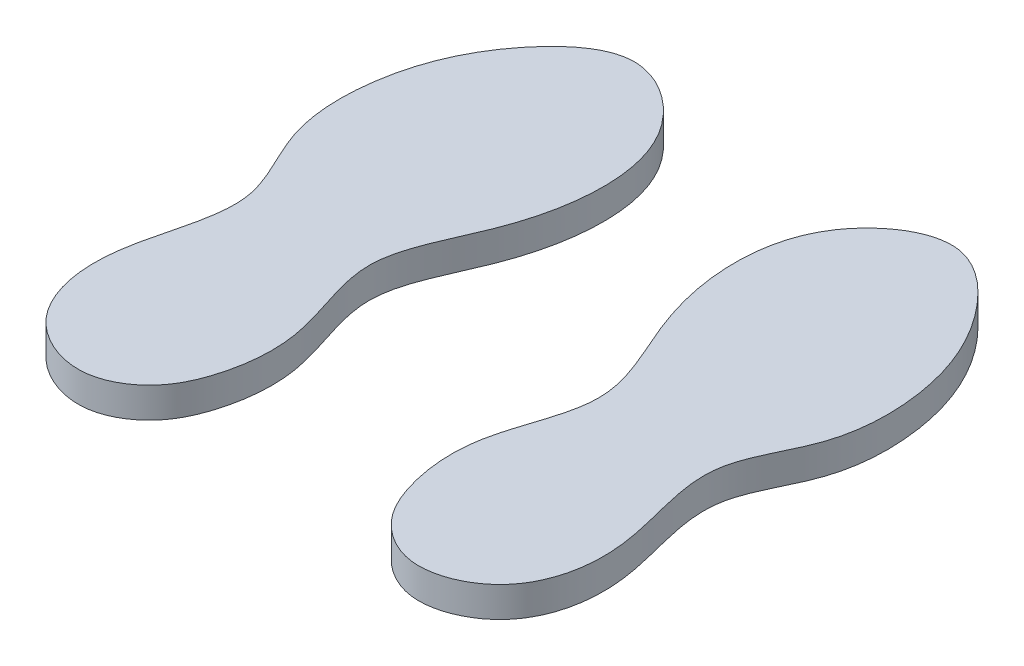
SolidWorks part; units mm, degrees
ref_plane "Front Plane" through (0, 0, 0) normal (0, 0, 1) x (1, 0, 0)
ref_plane "Top Plane" through (0, 0, 0) normal (0, 1, 0) x (1, 0, 0)
ref_plane "Right Plane" through (0, 0, 0) normal (1, 0, 0) x (0, 0, -1)
sketch "Sketch4" plane through (0, 0, 0) normal (0, 1, 0) x (1, 0, 0)
  line L0 (56.4057, 205.7862) -> (275.739, 205.7862) construction
  line L1 (106.5441, 392.4491) -> (106.5441, 34.2507) construction
  line L2 (43.5276, 392.4491) -> (169.5606, 392.4491) construction
  line L3 (43.5276, 392.4491) -> (43.5276, 34.2507) construction
  line L4 (43.5276, 34.2507) -> (169.5606, 34.2507) construction
  line L5 (169.5606, 392.4491) -> (169.5606, 34.2507) construction
  line L6 (58.6245, 364.3793) -> (149.0935, 364.3793) construction
  line L7 (0, 409.6507) -> (0, 0) construction
  line L8 (43.5276, 303.4815) -> (179.4649, 290.0428) construction
  line L10 (56.1909, 249.4139) -> (174.4849, 237.7195) construction
  line L12 (75.6048, 190.165) -> (155.5664, 190.165) construction
  line L14 (60.6595, 126.0842) -> (166.5312, 115.6178) construction
  line L16 (63.3872, 78.3209) -> (161.7971, 68.5921) construction
  line L18 (76.1578, 52.0606) -> (151.5436, 52.0606) construction
  spline S0 degree 3 poles (48.6704, 365.5963) (106.3639, 405.5539) (161.1746, 358.1666) (182.8239, 300.1421) (179.3716, 236.9598) (143.3222, 183.7737) (170.2868, 125.5561) (167.4369, 76.3404) (147.6562, 42.9463) (109.8754, 26.3151) (74.5548, 48.6354) (59.7412, 83.871) (56.2023, 132.5815) (86.9019, 189.3363) (54.2529, 247.0242) (39.3999, 305.1123) (48.6704, 365.5963) (106.3639, 405.5539) (161.1746, 358.1666) knots -0.206989 -0.140857 -0.066138 0 0.060706 0.156337 0.218931 0.279881 0.369615 0.425901 0.449068 0.506703 0.548648 0.583423 0.640398 0.71876 0.793011 0.859143 0.933862 1 1.060706 1.156337 1.218931 only from (106.5441, 392.4491) to (106.5441, 392.4491)
  spline S1 degree 3 poles (-48.6704, 365.5963) (-106.3639, 405.5539) (-161.1746, 358.1666) (-182.8239, 300.1421) (-179.3716, 236.9598) (-143.3222, 183.7737) (-170.2868, 125.5561) (-167.4369, 76.3404) (-147.6562, 42.9463) (-109.8754, 26.3151) (-74.5548, 48.6354) (-59.7412, 83.871) (-56.2023, 132.5815) (-86.9019, 189.3363) (-54.2529, 247.0242) (-39.3999, 305.1123) (-48.6704, 365.5963) (-106.3639, 405.5539) (-161.1746, 358.1666) knots -0.206989 -0.140857 -0.066138 0 0.060706 0.156337 0.218931 0.279881 0.369615 0.425901 0.449068 0.506703 0.548648 0.583423 0.640398 0.71876 0.793011 0.859143 0.933862 1 1.060706 1.156337 1.218931 only from (-106.5441, 392.4491) to (-106.5441, 392.4491)
extrude "Boss-Extrude4" add sketch "Sketch4" along normal blind 20
sketch "Sketch5" plane through (0, 0, 0) normal (1, 0, 0) x (0, 0, -1)
  line L0 (33.8643, 0) -> (33.8643, 20)
  line L1 (33.8643, 20) -> (33.8643, 0) construction
  line L2 (33.8643, 0) -> (392.5103, 0) construction
  line L3 (33.8643, 20) -> (392.5103, 20)
  line L4 (392.5103, 20) -> (33.8643, 20) construction
  line L5 (392.5103, 20) -> (392.5103, 0)
  line L6 (33.8643, 20) -> (33.8643, 10)
  spline S0 degree 3 poles (33.8643, 10) (73.221, 2.9649) (125.3911, 1.085) (244.8012, -2.1004) (324.6615, 1.53) (392.5103, 0) knots 0 0 0 0 0.333571 0.433571 1 1 1 1
  point P7 (33.8643, 10)
  point P15 (0, 0)
  point P16 (0, 0)
  point P17 (0, 0)
